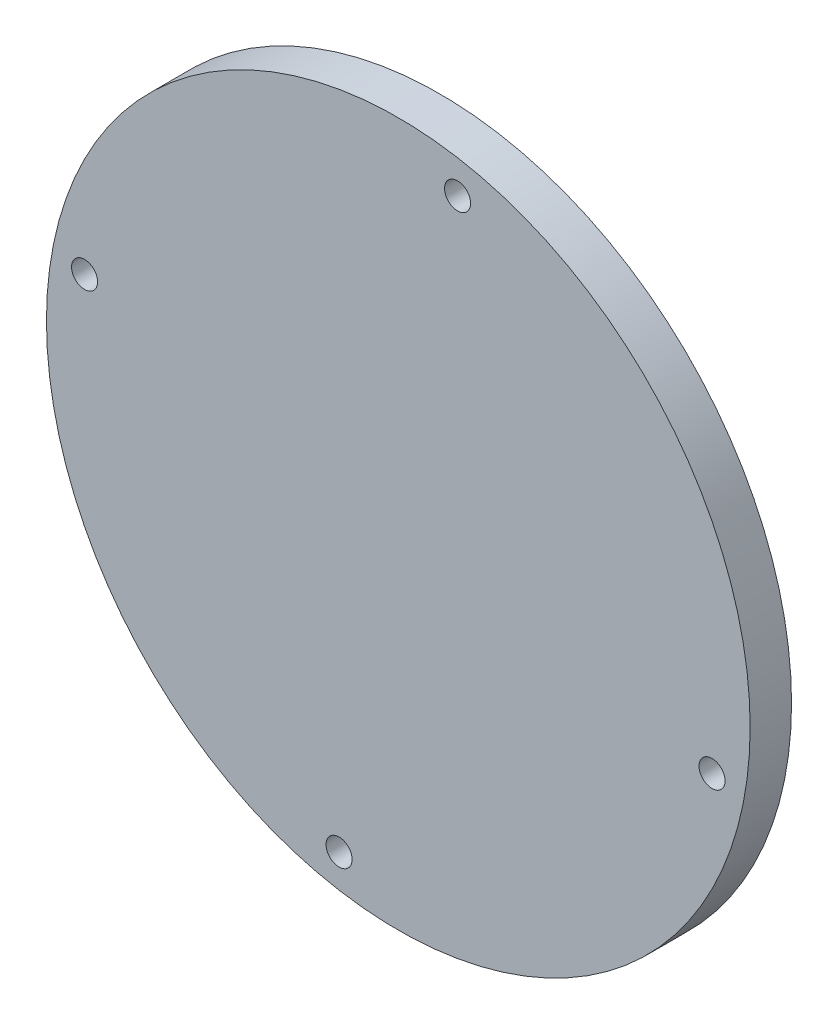
SolidWorks part; units mm, degrees
material "Acrylic (Medium-high impact)"
ref_plane "Front Plane" through (0, 0, 0) normal (0, 0, 1) x (1, 0, 0)
ref_plane "Top Plane" through (0, 0, 0) normal (0, 1, 0) x (1, 0, 0)
ref_plane "Right Plane" through (0, 0, 0) normal (1, 0, 0) x (0, 0, -1)
sketch "Sketch1" plane through (0, 0, 0) normal (0, 0, 1) x (1, 0, 0)
  circle A0 centre (0, 0) radius 27
  dimension "D1" = 54
extrude "Boss-Extrude1" add sketch "Sketch1" along normal blind 3.175
hole_wizard "Ø1.5mm Dowel Hole1" positions "Sketch4" profile "Sketch5" hole size "Ø1.5" standard "ANSI Metric" end condition through all
sketch "Sketch4" plane through (0, 0, 0) normal (0, 0, -1) x (-1, 0, 0)
  point P0 (-24.0747, -4.5451)
  point P3 (4.5451, -24.0747)
  point P6 (24.0747, 4.5451)
  point P9 (-4.5451, 24.0747)
sketch "Sketch5" plane through (24.0747, -4.5451, 0) normal (1, 0, 0) x (0, 1, 0)
  line L0 (0, 0) -> (0, 3.175)
  line L1 (0, 3.175) -> (1, 3.175)
  line L2 (1, 3.175) -> (1, 0)
  line L5 (1, 0) -> (0, 0)
  line L11 (0, -6.35) -> (0, 107.95) construction
  dimension "Thru Hole Dia." = 2
  dimension "Thru Hole Depth" = 3.175
